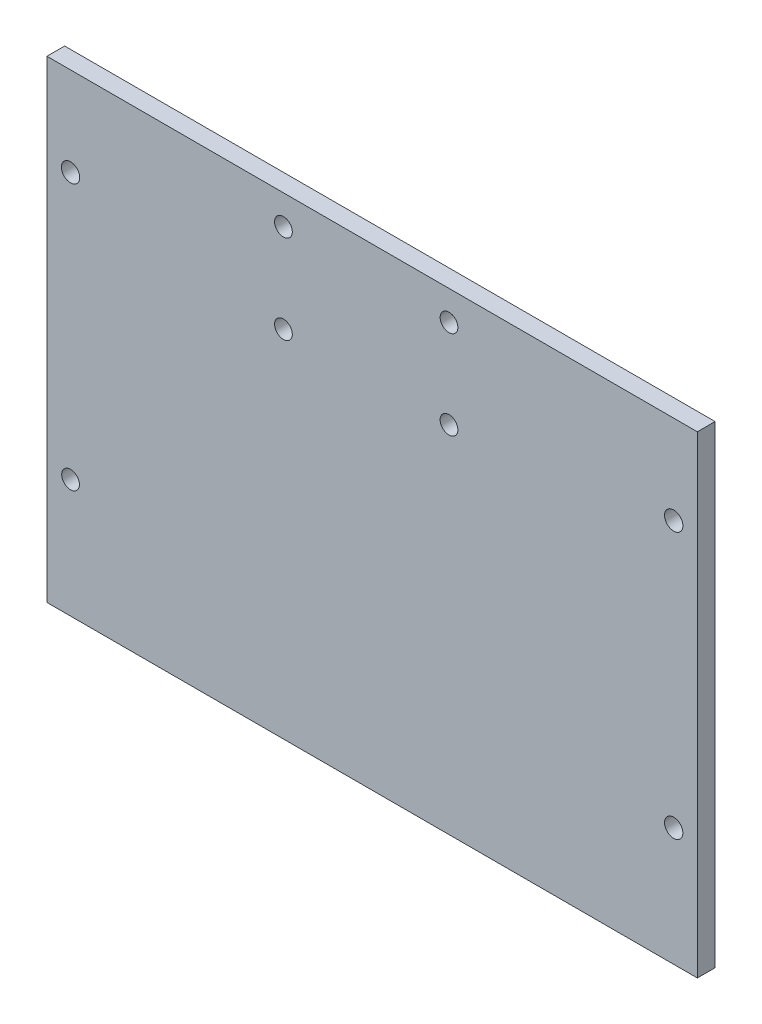
SolidWorks part; units mm, degrees
ref_plane "前视基准面" through (0, 0, 0) normal (0, 0, 1) x (1, 0, 0)
ref_plane "上视基准面" through (0, 0, 0) normal (0, 1, 0) x (1, 0, 0)
ref_plane "右视基准面" through (0, 0, 0) normal (1, 0, 0) x (0, 0, -1)
other "Configuration Table"
sketch "草图1" plane through (0, 0, 0) normal (0, 0, 1) x (1, 0, 0)
  line L1 (55, -40) -> (-55, -40)
  line L2 (55, -40) -> (55, 40)
  line L3 (55, 40) -> (-55, 40)
  line L4 (-55, -40) -> (-55, 40)
  line L5 (55, -40) -> (-55, 40) construction
  line L6 (55, 40) -> (-55, -40) construction
  point P0 (0, 0)
  dimension "D1" = 80
  dimension "D2" = 110
extrude "凸台-拉伸1" add sketch "草图1" along normal blind 3
sketch "草图2" plane through (0, 0, 0) normal (0, 0, -1) x (-1, 0, 0)
  line L0 (55, -40) -> (-55, -40) construction
  line L1 (-55, -40) -> (-55, 40) construction
  circle A0 centre (-13, 20.02) radius 1.5
  circle A1 centre (-13, 35.02) radius 1.5
  circle A2 centre (15, 20.02) radius 1.5
  circle A3 centre (15, 35.02) radius 1.5
  point P12 (0, 0)
  point P13 (0, 0)
  point P14 (-13.1057, 6.5163)
  dimension "D1" = 28
  dimension "D2" = 15
  dimension "D3" = 15
  dimension "D4" = 28
  dimension "D5" = 60.02
  dimension "D6" = 60.02
  dimension "D7" = 75.02
  dimension "D8" = 42
extrude "切除-拉伸1" cut sketch "草图2" against normal blind 10
sketch "草图3" plane through (0, 0, 0) normal (0, 0, -1) x (-1, 0, 0)
  line L1 (55, 40) -> (55, -40) construction
  line L2 (-55, 40) -> (55, 40) construction
  line L3 (-55, -40) -> (-55, 40) construction
  line L4 (55, -40) -> (-55, -40) construction
  circle A0 centre (-51, -20) radius 1.55
  circle A1 centre (-51, 25) radius 1.55
  circle A2 centre (51, -20) radius 1.5
  circle A3 centre (51, 25) radius 1.55
  dimension "D1" = 4
  dimension "D2" = 15
  dimension "D3" = 15
  dimension "D4" = 4
  dimension "D5" = 4
  dimension "D6" = 20
  dimension "D7" = 4
  dimension "D8" = 20
extrude "切除-拉伸2" cut sketch "草图3" against normal blind 10
